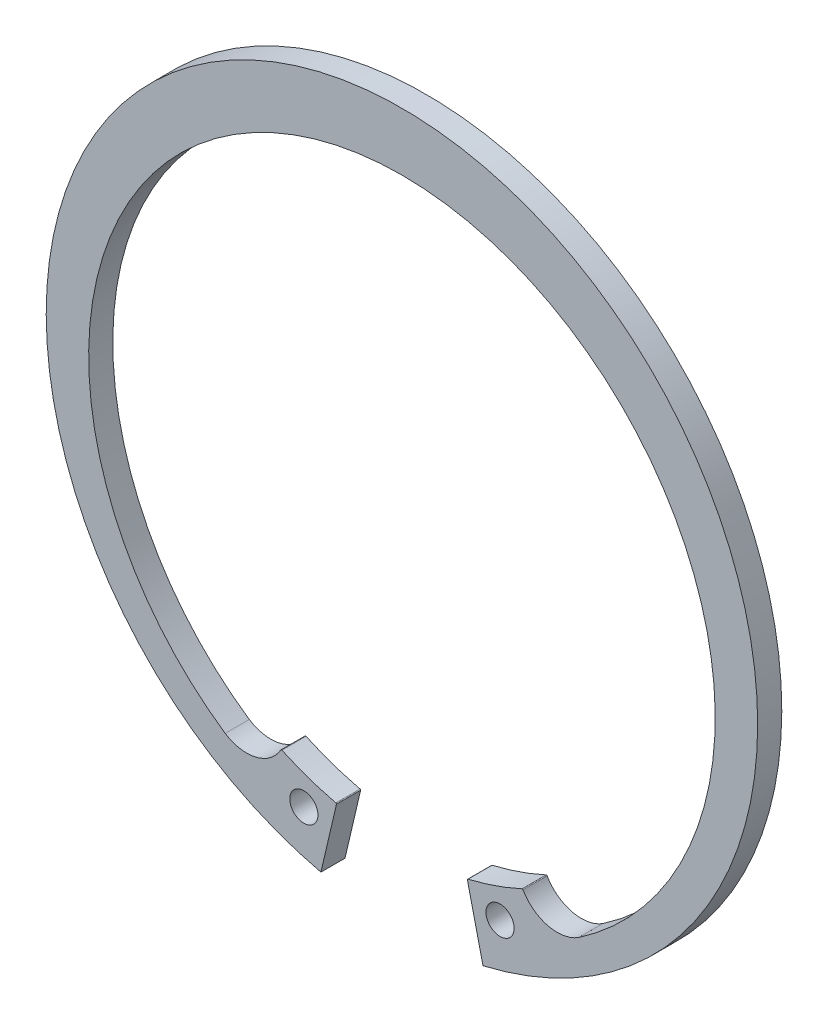
SolidWorks part; units mm, degrees
extrude "Body" add sketch "BodySke" against normal blind 3
sketch "BodySke" plane through (0, 0, 0) normal (0, 0, 1) x (1, 0, 0)
  line L0 (-1.5431, 0) -> (1.5431, 0) construction
  line L1 (0, 0) -> (0, 37.05) construction
  line L2 (10.0816, -43.0862) -> (8.8683, -37.9009)
  line L3 (-10.0816, -43.0862) -> (-8.8683, -37.9009)
  line L4 (0, 0) -> (20.8548, -39.0274) construction
  line L5 (0, 0) -> (-20.8548, -39.0274) construction
  line L6 (-11.8045, -35.4166) -> (-12.6019, -38.8246) construction
  line L7 (12.0322, -36.3897) -> (12.3742, -37.8514) construction
  arc A0 (-8.8683, -37.9009) -> (-14.8734, -34.9756) centre (-12.2032, -37.1206) ccw
  arc A1 (14.8734, -34.9756) -> (8.8683, -37.9009) centre (12.2032, -37.1206) ccw
  arc A2 (19.1582, -35.8523) -> (-19.1582, -35.8523) centre (0, -1.9185) ccw construction
  arc A3 (10.0816, -43.0862) -> (-10.0816, -43.0862) centre (0, 0) ccw
  circle A4 centre (12.2032, -37.1206) radius 1.75
  circle A5 centre (-12.2032, -37.1206) radius 1.75
  circle A6 centre (12.2032, -37.1206) radius 3.425 construction
  arc A7 (19.234, -35.8094) -> (-19.234, -35.8094) centre (0, -1.9185) ccw
  arc A8 (-12.2032, -37.1206) -> (12.2032, -37.1206) centre (0, 0) ccw construction
  arc A9 (-19.234, -35.8094) -> (-14.8734, -34.9756) centre (-17.5435, -32.8306) ccw
  arc A10 (14.8734, -34.9756) -> (19.234, -35.8094) centre (17.5435, -32.8306) ccw
  dimension "HoleDia" = 3.5
  dimension "HoleOffsetRad" = 39.075
  dimension "GrooveDia" = 88.5
  dimension "TipRad" = 3.425
  dimension "FilletRad" = 3.425
  dimension "LargeRad" = 37.05
  dimension "SmallRad" = 40.65
  dimension "SmallAngle" = 56.237
  dimension "GapAngle" = 26.339
ref_plane "Plane1" through (0, 0, 0) normal (0, 0, 1) x (1, 0, 0)
ref_plane "Plane2" through (0, 0, 0) normal (0, 1, 0) x (1, 0, 0)
ref_plane "Plane3" through (0, 0, 0) normal (1, 0, 0) x (0, 0, -1)
other "Configuration Table"
sketch "Clipboard" plane through (0, 0, 0) normal (0, 0, 1) x (1, 0, 0)
  line L0 (0, 0) -> (7.2, 0)
  line L1 (0, 0) -> (0, 3.6)
  line L2 (0, 0) -> (0, -8.6)
  circle A0 centre (0, 0) radius 1.75
  circle A1 centre (0, 0) radius 42.5
  dimension "HoleDia" = 3.5
  dimension "BoreDia" = 85
  dimension "LargeSection" = 7.2
  dimension "SmallSection" = 3.6
  dimension "LugSection" = 8.6
sketch "ModLugSke" plane through (0, 0, 0) normal (0, 0, 1) x (1, 0, 0)
  line L0 (10.0816, -43.0862) -> (8.145, -34.8097)
  line L1 (-10.0816, -43.0862) -> (-8.145, -34.8097)
  line L2 (19.3208, -29.9605) -> (23.9816, -37.188) construction
  line L3 (-19.3208, -29.9605) -> (-23.9816, -37.188) construction
  line L4 (-10.0816, -43.0862) -> (-8.8683, -37.9009) construction
  line L5 (8.8683, -37.9009) -> (10.0816, -43.0862) construction
  line L6 (0, 0) -> (0, -18.0732) construction
  line L7 (21.9844, -34.091) -> (23.9816, -37.188)
  line L8 (-23.9816, -37.188) -> (-21.9844, -34.091)
  arc A0 (10.0816, -43.0862) -> (23.9816, -37.188) centre (0, 0) ccw
  arc A1 (-14.9328, -32.3718) -> (-8.2193, -34.6896) centre (0, 0) ccw
  arc A2 (10.0816, -43.0862) -> (-10.0816, -43.0862) centre (0, 0) ccw construction
  arc A3 (14.8734, -34.9756) -> (8.8683, -37.9009) centre (12.2032, -37.1206) ccw construction
  arc A4 (-14.9328, -32.3718) -> (-15.0614, -32.4127) centre (-14.9747, -32.4626) ccw
  arc A5 (-21.9844, -34.091) -> (-15.0614, -32.4127) centre (-19.3208, -29.9605) ccw
  arc A6 (19.234, -35.8094) -> (-19.234, -35.8094) centre (0, -1.9185) ccw construction
  arc A7 (15.0614, -32.4127) -> (21.9844, -34.091) centre (19.3208, -29.9605) ccw
  arc A8 (8.2193, -34.6896) -> (14.9328, -32.3718) centre (0, 0) ccw
  arc A9 (-23.9816, -37.188) -> (-10.0816, -43.0862) centre (0, 0) ccw
  circle A10 centre (-12.2032, -37.1206) radius 1.75
  circle A11 centre (-12.2032, -37.1206) radius 1.75 construction
  circle A12 centre (12.2032, -37.1206) radius 1.75
  circle A13 centre (12.2032, -37.1206) radius 1.75 construction
  arc A14 (-8.2193, -34.6896) -> (-8.145, -34.8097) centre (-8.2423, -34.7869) cw
  arc A15 (8.2193, -34.6896) -> (8.145, -34.8097) centre (8.2423, -34.7869) ccw
  arc A16 (14.9328, -32.3718) -> (15.0614, -32.4127) centre (14.9747, -32.4626) cw
  point P43 (8.1222, -34.7124)
  dimension "D1" = 0.1
extrude "ModLug" add sketch "ModLugSke" against normal through all
sketch "UnlSke" [suppressed] plane through (0, 0, 0) normal (0, 0, 1) x (1, 0, 0)
  line L0 (2.1178, -8.3352) -> (3.2259, -12.6966)
  line L1 (-2.1178, -8.3352) -> (-3.2259, -12.6966)
  line L2 (-3.2259, -12.6966) -> (-2.1422, -8.4315) construction
  line L3 (2.1422, -8.4315) -> (3.2259, -12.6966) construction
  arc A0 (2.1178, -8.3352) -> (-2.1178, -8.3352) centre (0, 0) ccw
  arc A1 (3.2259, -12.6966) -> (-3.2259, -12.6966) centre (0, 0) ccw
  arc A2 (3.2259, -12.6966) -> (-3.2259, -12.6966) centre (0, 0) ccw construction
  circle A4 centre (-4.4431, -9.5688) radius 1
  circle A5 centre (4.4431, -9.5688) radius 1
  circle A6 centre (4.4431, -9.5688) radius 1 construction
  circle A7 centre (-4.4431, -9.5688) radius 1 construction
  arc A8 (2.2134, -8.3103) -> (4.9183, -7.0548) centre (0, 0) ccw construction
extrude "Unlug" [suppressed] add sketch "UnlSke" against normal through all
equation "' \"BoreDia@Clipboard\" = 8"
equation "' \"Thickness@Body\" = 0.8"
equation "' \"GrooveDia@BodySke\" = 8.4"
equation "' \"LugSection@Clipboard\" = 2.4"
equation "' \"LargeSection@Clipboard\" = 1.1"
equation "' \"HoleDia@Clipboard\" = 1.0"
equation "' \"BoreDia@Clipboard\" = 25"
equation "' \"Thickness@Body\" = 1.2"
equation "' \"GrooveDia@BodySke\" = 26.2"
equation "' \"LugSection@Clipboard\" = 4.5"
equation "' \"LargeSection@Clipboard\" = 2.7"
equation "' \"HoleDia@Clipboard\" = 2"
equation "\"SmallSection@Clipboard\" = \"LargeSection@Clipboard\" * 0.5"
equation "\"TipRad@BodySke\" = (\"LugSection@Clipboard\" - (\"GrooveDia@BodySke\" / 2  -  \"BoreDia@Clipboard\" / 2 ) ) / 2"
equation "\"HoleOffsetRad@BodySke\" = (\"GrooveDia@BodySke\" / 2) - \"LugSection@Clipboard\"  + \"TipRad@BodySke\""
equation "\"LargeRad@BodySke\" =  \"GrooveDia@BodySke\" / 2 -  \"LargeSection@Clipboard\""
equation "\"SmallRad@BodySke\" =  \"GrooveDia@BodySke\" / 2 -  \"SmallSection@Clipboard\""
equation "\"HoleDia@BodySke\" =  \"HoleDia@Clipboard\""
equation "\"FilletRad@BodySke\" = \"TipRad@BodySke\" * 1.0"
equation "\"GapAngle@BodySke\" = 360 - 0.965 * 360 * ( \"BoreDia@Clipboard\" /  \"GrooveDia@BodySke\")"
equation "\"LugAng@ModLugSke\" = \"GapAngle@BodySke\"  + 2 * 360 * (\"LugSection@Clipboard\" / (\"BoreDia@Clipboard\" * 3.1416))"
